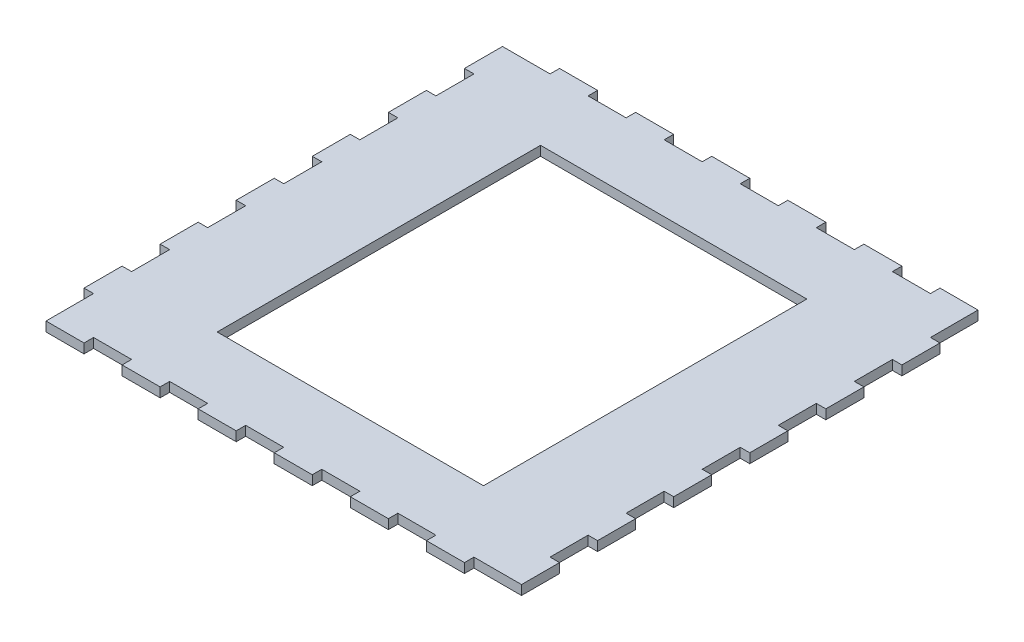
SolidWorks part; units mm, degrees
ref_plane "Front Plane" through (0, 0, 0) normal (0, 0, 1) x (1, 0, 0)
ref_plane "Top Plane" through (0, 0, 0) normal (0, 1, 0) x (1, 0, 0)
ref_plane "Right Plane" through (0, 0, 0) normal (1, 0, 0) x (0, 0, -1)
sketch "Sketch1" plane through (0, 0, 0) normal (0, 1, 0) x (1, 0, 0)
  line L0 (-65.2925, -101.6) -> (-39.8925, -101.6)
  line L1 (-97.0425, 152.4) -> (-97.0425, 127)
  line L2 (-97.0425, 203.2) -> (-97.0425, 177.8)
  line L3 (-90.6925, -107.95) -> (-65.2925, -107.95)
  line L4 (188.7075, 209.55) -> (214.1075, 209.55)
  line L5 (-90.6925, 177.8) -> (-90.6925, 152.4)
  line L6 (-97.0425, 203.2) -> (-65.2925, 203.2)
  line L7 (214.1075, 209.55) -> (214.1075, 177.8)
  line L8 (-65.2925, 209.55) -> (-65.2925, 203.2)
  line L9 (-39.8925, 209.55) -> (-39.8925, 203.2)
  line L10 (-14.4925, 209.55) -> (-14.4925, 203.2)
  line L11 (36.3075, 209.55) -> (36.3075, 203.2)
  line L12 (61.7075, 209.55) -> (61.7075, 203.2)
  line L13 (87.1075, 209.55) -> (87.1075, 203.2)
  line L14 (112.5075, 209.55) -> (112.5075, 203.2)
  line L15 (10.9075, 209.55) -> (10.9075, 203.2)
  line L16 (137.9075, 209.55) -> (137.9075, 203.2)
  line L17 (163.3075, 209.55) -> (163.3075, 203.2)
  line L18 (188.7075, 209.55) -> (188.7075, 203.2)
  line L19 (-97.0425, -76.2) -> (-90.6925, -76.2)
  line L20 (-97.0425, -50.8) -> (-90.6925, -50.8)
  line L21 (-97.0425, -25.4) -> (-90.6925, -25.4)
  line L22 (-97.0425, 0) -> (-90.6925, 0)
  line L23 (-97.0425, 25.4) -> (-90.6925, 25.4)
  line L24 (-97.0425, 50.8) -> (-90.6925, 50.8)
  line L25 (-97.0425, 76.2) -> (-90.6925, 76.2)
  line L26 (-97.0425, 101.6) -> (-90.6925, 101.6)
  line L27 (-97.0425, 127) -> (-90.6925, 127)
  line L28 (-97.0425, 152.4) -> (-90.6925, 152.4)
  line L29 (-97.0425, 177.8) -> (-90.6925, 177.8)
  line L30 (-39.8925, -107.95) -> (-14.4925, -107.95)
  line L31 (10.9075, -107.95) -> (36.3075, -107.95)
  line L32 (61.7075, -107.95) -> (87.1075, -107.95)
  line L33 (112.5075, -107.95) -> (137.9075, -107.95)
  line L34 (163.3075, -107.95) -> (188.7075, -107.95)
  line L35 (220.4575, -76.2) -> (220.4575, -101.6)
  line L36 (220.4575, -25.4) -> (220.4575, -50.8)
  line L37 (220.4575, 25.4) -> (220.4575, 0)
  line L38 (220.4575, 76.2) -> (220.4575, 50.8)
  line L39 (220.4575, 127) -> (220.4575, 101.6)
  line L40 (220.4575, 177.8) -> (220.4575, 152.4)
  line L41 (137.9075, 209.55) -> (163.3075, 209.55)
  line L42 (87.1075, 209.55) -> (112.5075, 209.55)
  line L43 (36.3075, 209.55) -> (61.7075, 209.55)
  line L44 (-14.4925, 209.55) -> (10.9075, 209.55)
  line L45 (-65.2925, 209.55) -> (-39.8925, 209.55)
  line L46 (-97.0425, 101.6) -> (-97.0425, 76.2)
  line L47 (-97.0425, 50.8) -> (-97.0425, 25.4)
  line L48 (-97.0425, 0) -> (-97.0425, -25.4)
  line L49 (-97.0425, -50.8) -> (-97.0425, -76.2)
  line L50 (-39.8925, 203.2) -> (-14.4925, 203.2)
  line L51 (10.9075, 203.2) -> (36.3075, 203.2)
  line L52 (61.7075, 203.2) -> (87.1075, 203.2)
  line L53 (112.5075, 203.2) -> (137.9075, 203.2)
  line L54 (163.3075, 203.2) -> (188.7075, 203.2)
  line L66 (-90.6925, -76.2) -> (-90.6925, -107.95)
  line L67 (-90.6925, 127) -> (-90.6925, 101.6)
  line L68 (-90.6925, 76.2) -> (-90.6925, 50.8)
  line L69 (-90.6925, 25.4) -> (-90.6925, 0)
  line L70 (-90.6925, -25.4) -> (-90.6925, -50.8)
  line L71 (-14.4925, -101.6) -> (10.9075, -101.6)
  line L72 (36.3075, -101.6) -> (61.7075, -101.6)
  line L73 (87.1075, -101.6) -> (112.5075, -101.6)
  line L74 (137.9075, -101.6) -> (163.3075, -101.6)
  line L75 (188.7075, -101.6) -> (220.4575, -101.6)
  line L76 (214.1075, -50.8) -> (214.1075, -76.2)
  line L77 (214.1075, 0) -> (214.1075, -25.4)
  line L78 (214.1075, 50.8) -> (214.1075, 25.4)
  line L79 (214.1075, 76.2) -> (220.4575, 76.2)
  line L80 (214.1075, 101.6) -> (214.1075, 76.2)
  line L81 (214.1075, 152.4) -> (214.1075, 127)
  line L82 (214.1075, 177.8) -> (220.4575, 177.8)
  line L83 (214.1075, 152.4) -> (220.4575, 152.4)
  line L84 (214.1075, 127) -> (220.4575, 127)
  line L85 (214.1075, 101.6) -> (220.4575, 101.6)
  line L86 (214.1075, 50.8) -> (220.4575, 50.8)
  line L87 (214.1075, 25.4) -> (220.4575, 25.4)
  line L88 (214.1075, 0) -> (220.4575, 0)
  line L89 (214.1075, -25.4) -> (220.4575, -25.4)
  line L90 (214.1075, -50.8) -> (220.4575, -50.8)
  line L91 (214.1075, -76.2) -> (220.4575, -76.2)
  line L92 (188.7075, -101.6) -> (188.7075, -107.95)
  line L93 (163.3075, -101.6) -> (163.3075, -107.95)
  line L94 (137.9075, -101.6) -> (137.9075, -107.95)
  line L95 (112.5075, -101.6) -> (112.5075, -107.95)
  line L96 (87.1075, -101.6) -> (87.1075, -107.95)
  line L97 (61.7075, -101.6) -> (61.7075, -107.95)
  line L98 (36.3075, -101.6) -> (36.3075, -107.95)
  line L99 (10.9075, -101.6) -> (10.9075, -107.95)
  line L100 (-14.4925, -101.6) -> (-14.4925, -107.95)
  line L101 (-39.8925, -101.6) -> (-39.8925, -107.95)
  line L102 (-65.2925, -101.6) -> (-65.2925, -107.95)
  dimension "D3" = 6.35
  dimension "D4" = 6.35
  dimension "D7" = 25.4
  dimension "D8" = 50.8
  dimension "D9" = 76.2
  dimension "D10" = 101.6
  dimension "D11" = 127
  dimension "D12" = 152.4
  dimension "D13" = 177.8
  dimension "D14" = 203.2
  dimension "D15" = 228.6
  dimension "D16" = 254
  dimension "D17" = 279.4
  dimension "D18" = 25.4
  dimension "D19" = 50.8
  dimension "D20" = 76.2
  dimension "D21" = 101.6
  dimension "D22" = 127
  dimension "D23" = 152.4
  dimension "D24" = 177.8
  dimension "D25" = 203.2
  dimension "D26" = 228.6
  dimension "D27" = 254
  dimension "D28" = 279.4
  dimension "D29" = 304.8
extrude "Boss-Extrude1" add sketch "Sketch1" along normal blind 6.35
sketch "Sketch2" plane through (0, 6.35, 0) normal (0, 1, 0) x (1, 0, 0)
  line L0 (-97.0425, 203.2) -> (220.4575, -101.6) construction
  line L1 (-90.6925, -107.95) -> (214.1075, 209.55) construction
  line L2 (61.7075, 50.8) -> (220.4575, 50.8) construction
  line L3 (214.1075, 50.8) -> (220.4575, 50.8) construction
  line L4 (61.7075, 50.8) -> (-97.0425, 50.8) construction
  line L5 (61.7075, 50.8) -> (61.7075, 209.55) construction
  line L6 (61.7075, 50.8) -> (61.7075, -107.95) construction
  line L8 (-27.1925, -57.15) -> (150.6075, -57.15)
  line L9 (-27.1925, -57.15) -> (-27.1925, 158.75)
  line L10 (-27.1925, 158.75) -> (150.6075, 158.75)
  line L11 (150.6075, -57.15) -> (150.6075, 158.75)
  line L12 (-27.1925, -57.15) -> (150.6075, 158.75) construction
  line L13 (-27.1925, 158.75) -> (150.6075, -57.15) construction
  point P8 (61.7075, 50.8)
  dimension "D1" = 215.9
  dimension "D2" = 177.8
extrude "Cut-Extrude2" cut sketch "Sketch2" against normal blind 6.35
